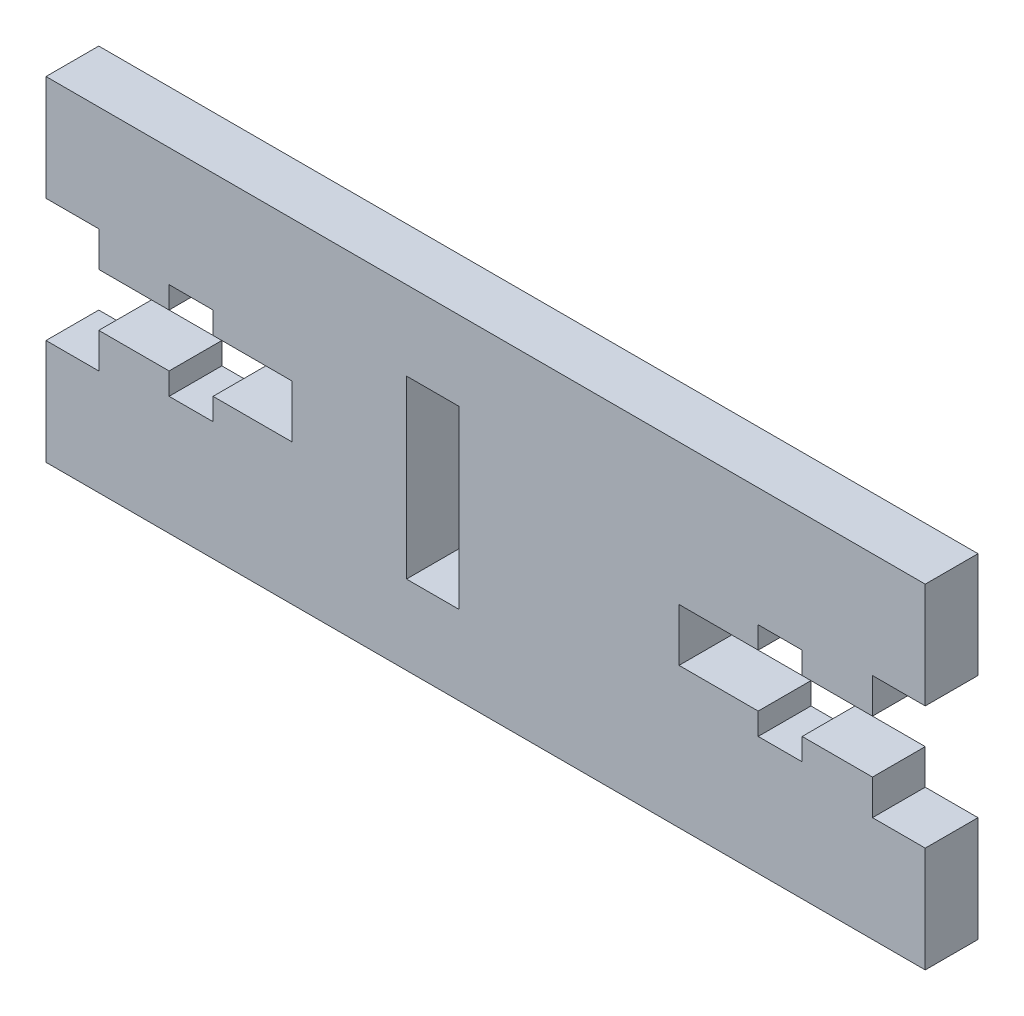
SolidWorks part; units mm, degrees
ref_plane "前视基准面" through (0, 0, 0) normal (0, 0, 1) x (1, 0, 0)
ref_plane "上视基准面" through (0, 0, 0) normal (0, 1, 0) x (1, 0, 0)
ref_plane "右视基准面" through (0, 0, 0) normal (1, 0, 0) x (0, 0, -1)
ref_plane "基准面1" through (0, 0, 3) normal (0, 0, 1) x (1, 0, 0)
sketch "草图1" plane through (0, 0, 3) normal (0, 0, 1) x (1, 0, 0)
  line L0 (19.0802, 4.5007) -> (16.0803, 4.5007)
  line L1 (16.0803, 4.5007) -> (16.0803, 14.4997)
  line L2 (16.0803, 14.4997) -> (19.0802, 14.4997)
  line L3 (19.0802, 14.4997) -> (19.0802, 4.5007)
  line L4 (42.58, 6) -> (42.58, 7.9995)
  line L5 (42.58, 7.9995) -> (38.581, 7.9995)
  line L6 (38.581, 7.9995) -> (38.581, 6.7496)
  line L7 (38.581, 6.7496) -> (36.0798, 6.7496)
  line L8 (36.0798, 6.7496) -> (36.0798, 7.9995)
  line L9 (36.0798, 7.9995) -> (31.58, 7.9995)
  line L10 (31.58, 7.9995) -> (31.58, 10.9995)
  line L11 (31.58, 10.9995) -> (36.0798, 10.9995)
  line L12 (36.0798, 10.9995) -> (36.0798, 12.2508)
  line L13 (36.0798, 12.2508) -> (38.581, 12.2508)
  line L14 (38.581, 12.2508) -> (38.581, 10.9995)
  line L15 (38.581, 10.9995) -> (42.58, 10.9995)
  line L16 (42.58, 10.9995) -> (42.58, 13.0004)
  line L17 (42.58, 13.0004) -> (45.5799, 13.0004)
  line L18 (45.5799, 13.0004) -> (45.5799, 19.0004)
  line L19 (45.5799, 19.0004) -> (-4.4194, 19.0004)
  line L20 (-4.4194, 19.0004) -> (-4.4194, 13.0004)
  line L21 (-4.4194, 13.0004) -> (-1.4194, 13.0004)
  line L22 (-1.4194, 13.0004) -> (-1.4194, 10.9995)
  line L23 (-1.4194, 10.9995) -> (2.5796, 10.9995)
  line L24 (2.5796, 10.9995) -> (2.5796, 12.2508)
  line L25 (2.5796, 12.2508) -> (5.0808, 12.2508)
  line L26 (5.0808, 12.2508) -> (5.0808, 10.9995)
  line L27 (5.0808, 10.9995) -> (9.5806, 10.9995)
  line L28 (9.5806, 10.9995) -> (9.5806, 7.9995)
  line L29 (9.5806, 7.9995) -> (5.0808, 7.9995)
  line L30 (5.0808, 7.9995) -> (5.0808, 6.7496)
  line L31 (5.0808, 6.7496) -> (2.5796, 6.7496)
  line L32 (2.5796, 6.7496) -> (2.5796, 7.9995)
  line L33 (2.5796, 7.9995) -> (-1.4194, 7.9995)
  line L34 (-1.4194, 7.9995) -> (-1.4194, 6)
  line L35 (-1.4194, 6) -> (-4.4193, 6)
  line L36 (-4.4193, 6) -> (-4.4193, 0)
  line L37 (-4.4193, 0) -> (45.5802, 0)
  line L38 (45.5802, 0) -> (45.5802, 6)
  line L39 (45.5802, 6) -> (42.58, 6)
extrude "凸台-拉伸1" add sketch "草图1" against normal blind 3
